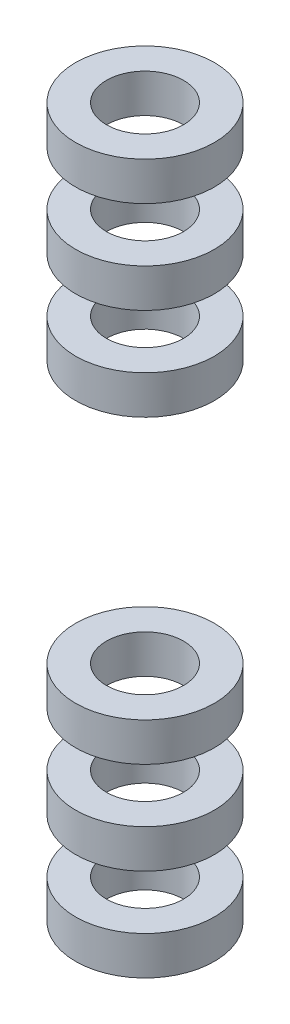
SolidWorks part; units mm, degrees
ref_plane "前视基准面" through (0, 0, 0) normal (0, 0, 1) x (1, 0, 0)
ref_plane "上视基准面" through (0, 0, 0) normal (0, 1, 0) x (1, 0, 0)
ref_plane "右视基准面" through (0, 0, 0) normal (1, 0, 0) x (0, 0, -1)
sketch "草图1" plane through (0, 0, 0) normal (0, 1, 0) x (1, 0, 0)
  circle A0 centre (0, 0) radius 25
  circle A1 centre (0, 0) radius 45
  dimension "D1" = 90
  dimension "D2" = 50
extrude "凸台-拉伸2" add sketch "草图1" along normal blind 460
sketch "草图2" plane through (0, 0, 0) normal (0, 0, 1) x (1, 0, 0)
  line L1 (45, 0) -> (45, 460) construction
  line L2 (45, 435) -> (45, 400)
  line L4 (45, 375) -> (45, 340)
  line L6 (45, 315) -> (45, 145)
  line L8 (45, 120) -> (45, 85)
  line L10 (45, 60) -> (45, 25)
  line L12 (45, 435) -> (-45, 435)
  line L13 (-45, 460) -> (-45, 0) construction
  line L14 (-45, 435) -> (-45, 400)
  line L15 (-45, 400) -> (45, 400)
  line L16 (45, 375) -> (-45, 375)
  line L17 (-45, 375) -> (-45, 340)
  line L18 (-45, 340) -> (45, 340)
  line L20 (45, 315) -> (-45, 315)
  line L21 (-45, 315) -> (-45, 145)
  line L22 (-45, 145) -> (45, 145)
  line L23 (45, 120) -> (-45, 120)
  line L24 (-45, 120) -> (-45, 85)
  line L25 (-45, 85) -> (45, 85)
  line L26 (45, 60) -> (-45, 60)
  line L27 (-45, 60) -> (-45, 25)
  line L28 (-45, 25) -> (45, 25)
  dimension "D2" = 35
  dimension "D3" = 170
extrude "切除-拉伸1" cut sketch "草图2" against normal blind 248 and the other way blind 154
